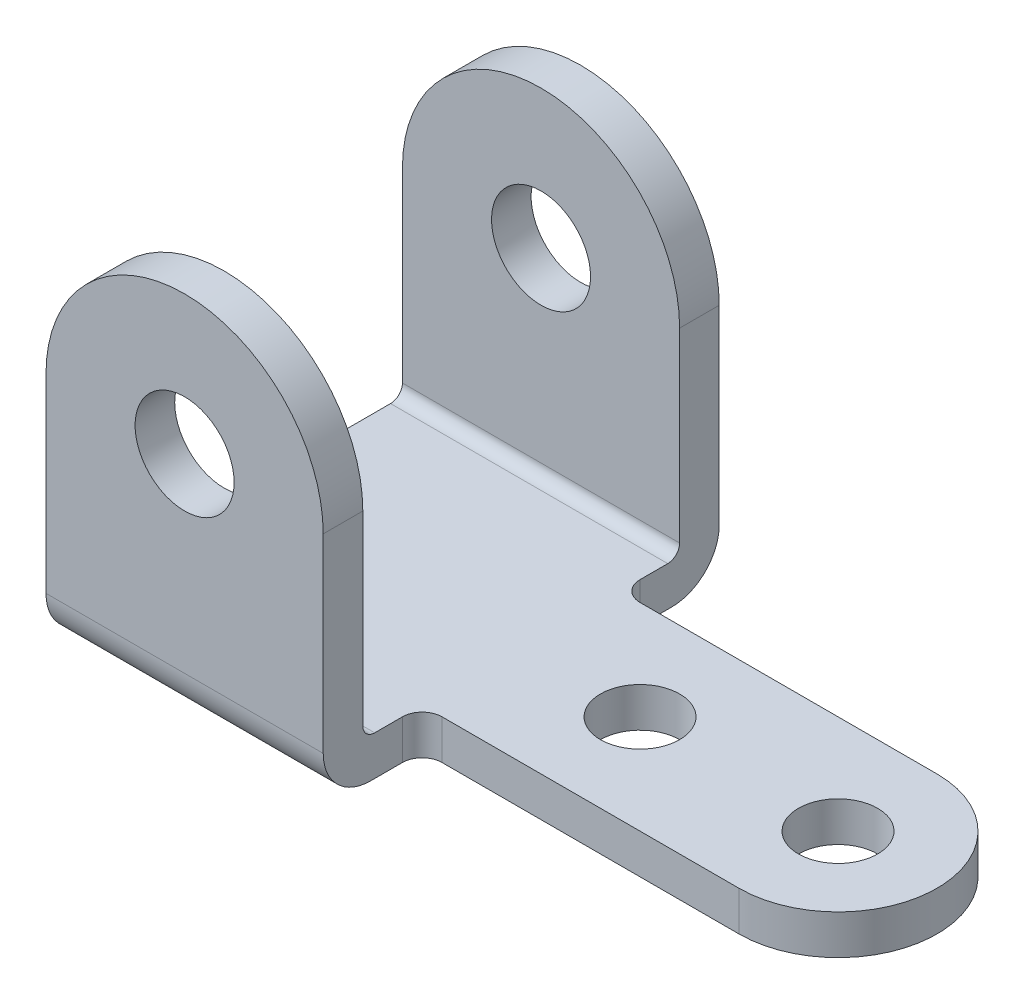
SolidWorks part; units mm, degrees
ref_plane "Plan de face" through (0, 0, 0) normal (0, 0, 1) x (1, 0, 0)
ref_plane "Plan de dessus" through (0, 0, 0) normal (0, 1, 0) x (1, 0, 0)
ref_plane "Plan de droite" through (0, 0, 0) normal (1, 0, 0) x (0, 0, -1)
sketch "Esquisse1" plane through (0, 0, 0) normal (0, 0, 1) x (1, 0, 0)
  line L0 (0, 0) -> (0, 60)
  line L1 (70, 60) -> (70, 0)
  line L2 (70, 0) -> (0, 0)
  arc A0 (0, 60) -> (70, 60) centre (35, 60) cw
  dimension "D2" = 35
  dimension "D1" = 60
extrude "Boss.-Extru.1" add sketch "Esquisse1" along normal blind 10 contours L2 L0 A0 L1
sketch "Esquisse4" plane through (0, 0, 0) normal (0, -1, 0) x (-1, 0, 0)
  line L0 (0, -10) -> (0, -90)
  line L1 (0, -90) -> (-70, -90)
  line L2 (-70, -90) -> (-70, -10)
  line L3 (0, -11.9445) -> (0, -10)
  line L5 (-70, -10) -> (0, -10)
  point P8 (0, 0)
  point P9 (0, 0)
  point P10 (-70, -90)
  point P11 (0, -90)
  point P12 (0, -10)
  point P13 (-70, -10)
  dimension "D1" = 80
  dimension "D2" = 70
extrude "Boss.-Extru.2" add sketch "Esquisse4" against normal blind 10 contours L0 L1 L2 L5
sketch "Esquisse6" plane through (0, 0, 90) normal (0, 0, 1) x (1, 0, 0)
  line L0 (0, 0) -> (0, 60)
  line L1 (70, 60) -> (70, 0)
  line L2 (70, 0) -> (0, 0)
  arc A0 (0, 60) -> (70, 60) centre (35, 60) cw
  point P5 (0, 0)
  dimension "D2" = 35
  dimension "D1" = 60
extrude "Boss.-Extru.3" add sketch "Esquisse6" along normal blind 10
sketch "Esquisse7" plane through (0, 0, 100) normal (0, 0, 1) x (1, 0, 0)
  line L0 (0, 60) -> (70, 60) construction
  circle A0 centre (35, 60) radius 12.5
  dimension "D1" = 25
extrude "Enlèv. mat.-Extru.2" cut sketch "Esquisse7" against normal through all
sketch "Esquisse9" plane through (0, 10, 0) normal (0, 1, 0) x (1, 0, 0)
  line L0 (70, -10) -> (70, -90) construction
  line L5 (70, -25) -> (150, -25)
  line L6 (150, -75) -> (70, -75)
  line L7 (70, -75) -> (70, -25)
  line L8 (70, 0) -> (0, 0) construction
  arc A0 (150, -25) -> (150, -75) centre (150, -50) cw
  point P5 (106.2777, -49.9996)
  point P13 (70, -75)
  point P14 (150, -75)
  dimension "D2" = 25
  dimension "D1" = 80
  dimension "D3" = 50
  dimension "D4" = 25
  dimension "D5" = 25
extrude "Boss.-Extru.4" add sketch "Esquisse9" against normal blind 10
sketch "Esquisse10" plane through (0, 10, 0) normal (0, 1, 0) x (1, 0, 0)
  line L0 (150, -25) -> (150, -75) construction
  circle A0 centre (150, -50) radius 10
  circle A1 centre (100, -50) radius 10
  point P8 (0, 0)
  point P9 (0, 0)
  dimension "D2" = 20
  dimension "D3" = 20
  dimension "D1" = 50
extrude "Enlèv. mat.-Extru.3" cut sketch "Esquisse10" against normal through all
fillet "Congé1" radius 5 2 edges at (70, 5, 25) (70, 5, 75)
fillet "Congé5" radius 12 1 edges at (35, 0, 100)
fillet "Congé6" radius 12 1 edges at (35, 0, 0)
fillet "Congé7" radius 3 1 edges at (35, 10, 10)
fillet "Congé8" radius 3 1 edges at (35, 10, 90)
